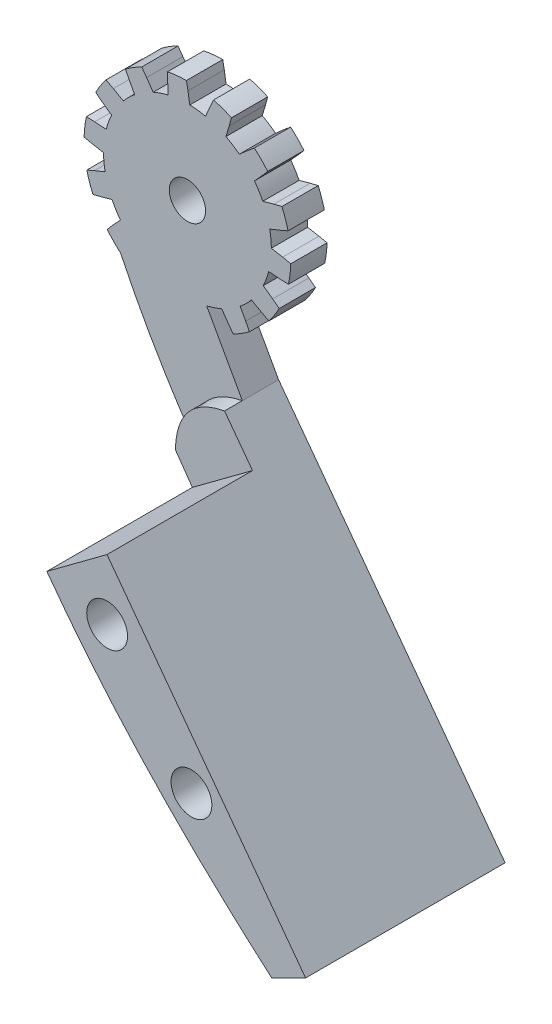
SolidWorks part; units mm, degrees
ref_plane "Front Plane" through (0, 0, 0) normal (0, 0, 1) x (1, 0, 0)
ref_plane "Top Plane" through (0, 0, 0) normal (0, 1, 0) x (1, 0, 0)
ref_plane "Right Plane" through (0, 0, 0) normal (1, 0, 0) x (0, 0, -1)
sketch "Sketch2" plane through (0, 0, 0) normal (0, 0, 1) x (1, 0, 0)
  line L595 (17.593, 3.4479) -> (18.4327, 3.8121)
  line L596 (16.415, 2.9762) -> (17.593, 3.4479)
  line L597 (15.6491, 5.2416) -> (16.8717, 5.5815)
  line L598 (16.8717, 5.5815) -> (17.7601, 5.8015)
  line L599 (5.2228, 10.175) -> (5.1635, 11.4426)
  line L600 (5.1635, 11.4426) -> (5.1467, 12.3577)
  line L601 (11.588, 9.3895) -> (11.9537, 10.6047)
  line L602 (11.9537, 10.6047) -> (12.1925, 11.4882)
  line L603 (9.3394, 10.2032) -> (9.8359, 11.371)
  line L604 (9.8359, 11.371) -> (10.2178, 12.2028)
  line L605 (14.7334, 6.7337) -> (15.5901, 7.6699)
  line L606 (15.5901, 7.6699) -> (16.1886, 8.3623)
  line L607 (13.0605, 8.4425) -> (14.0145, 9.2792)
  line L608 (14.0145, 9.2792) -> (14.7195, 9.8629)
  line L609 (-1.907, 1.1079) -> (-3.156, 1.3322)
  line L610 (-3.156, 1.3322) -> (-4.0519, 1.5194)
  line L611 (0.2752, 7.1388) -> (-0.8281, 7.7657)
  line L612 (-0.8281, 7.7657) -> (-1.6364, 8.1951)
  line L613 (-1.0184, 5.1275) -> (-2.0464, 5.8715)
  line L614 (-2.0464, 5.8715) -> (-2.7724, 6.4289)
  line L615 (3.5643, 9.6143) -> (2.8423, 10.6578)
  line L616 (2.8423, 10.6578) -> (2.3004, 11.3954)
  line L617 (1.5262, 8.3635) -> (0.9228, 9.4798)
  line L618 (0.9228, 9.4798) -> (0.5105, 10.297)
  line L619 (7.6018, 10.4176) -> (7.4041, 11.6711)
  line L620 (7.4041, 11.6711) -> (7.2358, 12.5707)
  line L621 (-0.0478, -4.3913) -> (-0.9045, -5.3274)
  line L622 (-0.9045, -5.3274) -> (-1.503, -6.0199)
  line L623 (1.6251, -6.1) -> (0.6711, -6.9367)
  line L624 (0.6711, -6.9367) -> (-0.0339, -7.5204)
  line L625 (-1.7294, -0.6337) -> (-2.9074, -1.1055)
  line L626 (-2.9074, -1.1055) -> (-3.7471, -1.4697)
  line L627 (-0.9635, -2.8991) -> (-2.1861, -3.239)
  line L628 (-2.1861, -3.239) -> (-3.0745, -3.459)
  line L629 (-1.6141, 3.4813) -> (-2.8801, 3.5674)
  line L630 (-2.8801, 3.5674) -> (-3.7947, 3.6036)
  line L631 (13.1594, -6.0211) -> (13.7628, -7.1374)
  line L632 (13.7628, -7.1374) -> (14.1751, -7.9546)
  line L633 (7.0838, -8.0751) -> (7.2815, -9.3286)
  line L634 (7.2815, -9.3286) -> (7.4497, -10.2283)
  line L635 (9.4628, -7.8326) -> (9.5221, -9.1001)
  line L636 (9.5221, -9.1001) -> (9.5389, -10.0152)
  line L637 (3.0976, -7.0471) -> (2.7319, -8.2622)
  line L638 (2.7319, -8.2622) -> (2.4931, -9.1458)
  line L639 (5.3462, -7.8607) -> (4.8497, -9.0285)
  line L640 (4.8497, -9.0285) -> (4.4678, -9.8603)
  line L641 (16.2997, -1.1388) -> (17.5657, -1.2249)
  line L642 (17.5657, -1.2249) -> (18.4803, -1.2611)
  line L643 (16.5926, 1.2345) -> (17.8416, 1.0103)
  line L644 (17.8416, 1.0103) -> (18.7375, 0.8231)
  line L645 (14.4104, -4.7963) -> (15.5137, -5.4232)
  line L646 (15.5137, -5.4232) -> (16.322, -5.8526)
  line L647 (15.704, -2.7851) -> (16.732, -3.529)
  line L648 (16.732, -3.529) -> (17.458, -4.0864)
  line L649 (11.1213, -7.2719) -> (11.8433, -8.3154)
  line L650 (11.8433, -8.3154) -> (12.3852, -9.053)
  arc A45 (12.3852, -9.053) -> (14.1751, -7.9546) centre (7.3428, 1.1712) ccw
  arc A46 (7.4497, -10.2283) -> (9.5389, -10.0152) centre (7.3428, 1.1712) ccw
  arc A48 (2.4931, -9.1458) -> (4.4678, -9.8603) centre (7.3428, 1.1712) ccw
  arc A50 (-1.503, -6.0199) -> (-0.0339, -7.5204) centre (7.3428, 1.1712) ccw
  arc A51 (5.3462, -7.8607) -> (7.0838, -8.0751) centre (7.3428, 1.1712) ccw
  arc A52 (-3.7471, -1.4697) -> (-3.0745, -3.459) centre (7.3428, 1.1712) ccw
  arc A53 (-3.7947, 3.6036) -> (-4.0519, 1.5194) centre (7.3428, 1.1712) ccw
  arc A54 (-1.6364, 8.1951) -> (-2.7724, 6.4289) centre (7.3428, 1.1712) ccw
  arc A55 (2.3004, 11.3954) -> (0.5105, 10.297) centre (7.3428, 1.1712) ccw
  arc A56 (7.2358, 12.5707) -> (5.1467, 12.3577) centre (7.3428, 1.1712) ccw
  arc A57 (12.1925, 11.4882) -> (10.2178, 12.2028) centre (7.3428, 1.1712) ccw
  arc A58 (16.1886, 8.3623) -> (14.7195, 9.8629) centre (7.3428, 1.1712) ccw
  arc A59 (18.4327, 3.8121) -> (17.7601, 5.8015) centre (7.3428, 1.1712) ccw
  arc A60 (18.4803, -1.2611) -> (18.7375, 0.8231) centre (7.3428, 1.1712) ccw
  arc A61 (16.322, -5.8526) -> (17.458, -4.0864) centre (7.3428, 1.1712) ccw
  arc A62 (1.6251, -6.1) -> (3.0976, -7.0471) centre (7.3428, 1.1712) ccw
  arc A63 (-0.9635, -2.8991) -> (-0.0478, -4.3913) centre (7.3428, 1.1712) ccw
  arc A64 (-1.907, 1.1079) -> (-1.7294, -0.6337) centre (7.3428, 1.1712) ccw
  arc A65 (-1.0184, 5.1275) -> (-1.6141, 3.4813) centre (7.3428, 1.1712) ccw
  arc A66 (1.5262, 8.3635) -> (0.2752, 7.1388) centre (7.3428, 1.1712) ccw
  arc A67 (5.2228, 10.175) -> (3.5643, 9.6143) centre (7.3428, 1.1712) ccw
  arc A68 (9.3394, 10.2032) -> (7.6018, 10.4176) centre (7.3428, 1.1712) ccw
  arc A69 (13.0605, 8.4425) -> (11.588, 9.3895) centre (7.3428, 1.1712) ccw
  arc A70 (15.6491, 5.2416) -> (14.7334, 6.7337) centre (7.3428, 1.1712) ccw
  arc A71 (16.5926, 1.2345) -> (16.415, 2.9762) centre (7.3428, 1.1712) ccw
  arc A72 (15.704, -2.7851) -> (16.2997, -1.1388) centre (7.3428, 1.1712) ccw
  arc A73 (13.1594, -6.0211) -> (14.4104, -4.7963) centre (7.3428, 1.1712) ccw
  arc A74 (9.4628, -7.8326) -> (11.1213, -7.2719) centre (7.3428, 1.1712) ccw
extrude "Boss-Extrude1" add sketch "Sketch2" against normal blind 4
sketch "Sketch5" plane through (0, 0, 0) normal (0, 0, 1) x (1, 0, 0)
  line L1 (11.4711, 11.5) -> (18.1778, 11.5) construction
  line L2 (-0.0339, -7.5204) -> (0.6711, -6.9367) construction
  line L6 (34.628, -50.4079) -> (38.3692, -48.5518)
  line L7 (-0.0339, -7.5204) -> (0.8657, -2.8432)
  line L8 (38.3692, -48.5518) -> (13.394, -14.9204)
  line L9 (0.8657, -2.8432) -> (9.4628, -7.8326)
  arc A1 (9.4628, -7.8326) -> (11.1213, -7.2719) centre (7.3428, 1.1712) ccw construction
  arc A2 (-1.503, -6.0199) -> (-0.0339, -7.5204) centre (7.3428, 1.1712) ccw construction
  spline S0 degree 1 poles (13.394, -14.9204) (9.4628, -7.8326) knots 0 0 1 1
  spline S1 degree 3 poles (34.628, -50.4079) (20.7375, -38.3435) (7.9572, -24.2645) (-0.0339, -7.5204) knots 0 0 0 0 1 1 1 1
extrude "Boss-Extrude3" add sketch "Sketch5" against normal up to surface (4 mm away) up to face at (7.3428, 1.1712, -4)
sketch "Sketch6" plane through (0, 0, -4) normal (0, 0, -1) x (-1, 0, 0)
  circle A2 centre (-7.3428, 1.1712) radius 2
  dimension "D1" = 4
extrude "Cut-Extrude1" cut sketch "Sketch6" against normal blind 18
sketch "Sketch7" plane through (0, 0, 0) normal (0, 0, 1) x (1, 0, 0)
  line L49 (34.628, -50.4079) -> (38.3692, -48.5518)
  line L50 (38.3692, -48.5518) -> (13.394, -14.9204)
  line L51 (13.394, -14.9204) -> (9.4628, -7.8326)
  line L52 (11.1213, -7.2719) -> (11.8433, -8.3154)
  line L53 (11.8433, -8.3154) -> (12.3852, -9.053)
  line L54 (14.1751, -7.9546) -> (13.7628, -7.1374)
  line L55 (13.7628, -7.1374) -> (13.1594, -6.0211)
  line L56 (14.4104, -4.7963) -> (15.5137, -5.4232)
  line L57 (15.5137, -5.4232) -> (16.322, -5.8526)
  line L58 (17.458, -4.0864) -> (16.732, -3.529)
  line L59 (16.732, -3.529) -> (15.704, -2.7851)
  line L60 (16.2997, -1.1388) -> (17.5657, -1.2249)
  line L61 (17.5657, -1.2249) -> (18.4803, -1.2611)
  line L62 (18.7375, 0.8231) -> (17.8416, 1.0103)
  line L63 (17.8416, 1.0103) -> (16.5926, 1.2345)
  line L64 (16.415, 2.9762) -> (17.593, 3.4479)
  line L65 (17.593, 3.4479) -> (18.4327, 3.8121)
  line L66 (17.7601, 5.8015) -> (16.8717, 5.5815)
  line L67 (16.8717, 5.5815) -> (15.6491, 5.2416)
  line L68 (14.7334, 6.7337) -> (15.5901, 7.6699)
  line L69 (15.5901, 7.6699) -> (16.1886, 8.3623)
  line L70 (14.7195, 9.8629) -> (14.0145, 9.2792)
  line L71 (14.0145, 9.2792) -> (13.0605, 8.4425)
  line L72 (11.588, 9.3895) -> (11.9537, 10.6047)
  line L73 (11.9537, 10.6047) -> (12.1925, 11.4882)
  line L74 (10.2178, 12.2028) -> (9.8359, 11.371)
  line L75 (9.8359, 11.371) -> (9.3394, 10.2032)
  line L76 (7.6018, 10.4176) -> (7.4041, 11.6711)
  line L77 (7.4041, 11.6711) -> (7.2358, 12.5707)
  line L78 (5.1467, 12.3577) -> (5.1635, 11.4426)
  line L79 (5.1635, 11.4426) -> (5.2228, 10.175)
  line L80 (3.5643, 9.6143) -> (2.8423, 10.6578)
  line L81 (2.8423, 10.6578) -> (2.3004, 11.3954)
  line L82 (0.5105, 10.297) -> (0.9228, 9.4798)
  line L83 (0.9228, 9.4798) -> (1.5262, 8.3635)
  line L84 (0.2752, 7.1388) -> (-0.8281, 7.7657)
  line L85 (-0.8281, 7.7657) -> (-1.6364, 8.1951)
  line L86 (-2.7724, 6.4289) -> (-2.0464, 5.8715)
  line L87 (-2.0464, 5.8715) -> (-1.0184, 5.1275)
  line L88 (-1.6141, 3.4813) -> (-2.8801, 3.5674)
  line L89 (-2.8801, 3.5674) -> (-3.7947, 3.6036)
  line L90 (-4.0519, 1.5194) -> (-3.156, 1.3322)
  line L91 (-3.156, 1.3322) -> (-1.907, 1.1079)
  line L92 (-1.7294, -0.6337) -> (-2.9074, -1.1055)
  line L93 (-2.9074, -1.1055) -> (-3.7471, -1.4697)
  line L94 (-3.0745, -3.459) -> (-2.1861, -3.239)
  line L95 (-2.1861, -3.239) -> (-0.9635, -2.8991)
  line L96 (-0.0478, -4.3913) -> (-0.9045, -5.3274)
  line L97 (-0.9045, -5.3274) -> (-1.503, -6.0199)
  line L98 (34.628, -50.4079) -> (38.3692, -48.5518)
  line L99 (38.3692, -48.5518) -> (13.394, -14.9204)
  arc A24 (-1.503, -6.0199) -> (-0.0339, -7.5204) centre (7.3428, 1.1712) ccw
  arc A25 (9.4628, -7.8326) -> (11.1213, -7.2719) centre (7.3428, 1.1712) ccw
  arc A26 (12.3852, -9.053) -> (14.1751, -7.9546) centre (7.3428, 1.1712) ccw
  arc A27 (13.1594, -6.0211) -> (14.4104, -4.7963) centre (7.3428, 1.1712) ccw
  arc A28 (16.322, -5.8526) -> (17.458, -4.0864) centre (7.3428, 1.1712) ccw
  arc A29 (15.704, -2.7851) -> (16.2997, -1.1388) centre (7.3428, 1.1712) ccw
  arc A30 (18.4803, -1.2611) -> (18.7375, 0.8231) centre (7.3428, 1.1712) ccw
  arc A31 (16.5926, 1.2345) -> (16.415, 2.9762) centre (7.3428, 1.1712) ccw
  arc A32 (18.4327, 3.8121) -> (17.7601, 5.8015) centre (7.3428, 1.1712) ccw
  arc A33 (15.6491, 5.2416) -> (14.7334, 6.7337) centre (7.3428, 1.1712) ccw
  arc A34 (16.1886, 8.3623) -> (14.7195, 9.8629) centre (7.3428, 1.1712) ccw
  arc A35 (13.0605, 8.4425) -> (11.588, 9.3895) centre (7.3428, 1.1712) ccw
  arc A36 (12.1925, 11.4882) -> (10.2178, 12.2028) centre (7.3428, 1.1712) ccw
  arc A37 (9.3394, 10.2032) -> (7.6018, 10.4176) centre (7.3428, 1.1712) ccw
  arc A38 (7.2358, 12.5707) -> (5.1467, 12.3577) centre (7.3428, 1.1712) ccw
  arc A39 (5.2228, 10.175) -> (3.5643, 9.6143) centre (7.3428, 1.1712) ccw
  arc A40 (2.3004, 11.3954) -> (0.5105, 10.297) centre (7.3428, 1.1712) ccw
  arc A41 (1.5262, 8.3635) -> (0.2752, 7.1388) centre (7.3428, 1.1712) ccw
  arc A42 (-1.6364, 8.1951) -> (-2.7724, 6.4289) centre (7.3428, 1.1712) ccw
  arc A43 (-1.0184, 5.1275) -> (-1.6141, 3.4813) centre (7.3428, 1.1712) ccw
  arc A44 (-3.7947, 3.6036) -> (-4.0519, 1.5194) centre (7.3428, 1.1712) ccw
  arc A45 (-1.907, 1.1079) -> (-1.7294, -0.6337) centre (7.3428, 1.1712) ccw
  arc A46 (-3.7471, -1.4697) -> (-3.0745, -3.459) centre (7.3428, 1.1712) ccw
  arc A47 (-0.9635, -2.8991) -> (-0.0478, -4.3913) centre (7.3428, 1.1712) ccw
  spline S0 degree 2 poles (7.978, -21.3451) (8.1121, -15.9213) (13.394, -14.9204) knots 0 0 0 1 1 1
  spline S1 degree 3 poles (2689.3147, 1264.9891) (-3237.4149, -692.61) (3465.2731, 248.2767) (-2933.8872, -462.9976) knots -8.084515 -8.084515 -8.084515 -8.084515 11.039067 11.039067 11.039067 11.039067 only from (-0.0339, -7.5204) to (34.628, -50.4079)
  spline S2 degree 3 poles (7.978, -21.3451) (15.4138, -32.2101) (24.7396, -41.8194) (34.628, -50.4079) knots 0.288119 0.288119 0.288119 0.288119 1 1 1 1
  dimension "D1" = 0
extrude "Boss-Extrude4" add sketch "Sketch7" along normal blind 18
sketch "Sketch8" plane through (0, 0, -4) normal (0, 0, -1) x (-1, 0, 0)
  circle A2 centre (-16.4902, -25.7466) radius 2.25
  circle A3 centre (-25.7856, -37.2154) radius 2.25
  point P1 (-16.4902, -25.7466)
extrude "Cut-Extrude2" cut sketch "Sketch8" against normal through all
sketch "Sketch10" plane through (1.4914, 1.1075, 0) normal (0.8028, 0.5962, 0) x (0, 0, -1)
  line L0 (0, -19.1331) -> (-18, -19.1331) construction
  line L1 (-27.1888, -7.44) -> (-1.9586, -7.44)
  line L2 (-27.1888, -7.44) -> (-27.1888, -25.1331)
  line L3 (-27.1888, -25.1331) -> (-1.9586, -25.1331)
  line L4 (-1.9586, -7.44) -> (-1.9586, -25.1331)
  dimension "D1" = 6
extrude "Cut-Extrude4" cut sketch "Sketch10" against normal through all
